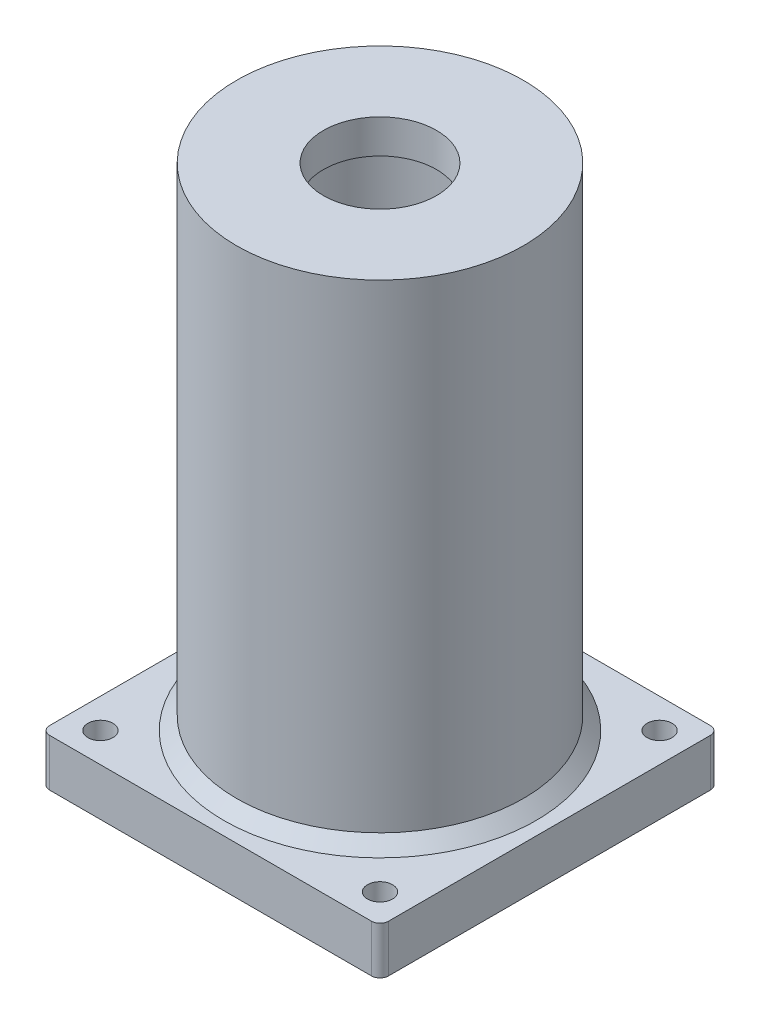
SolidWorks part; units mm, degrees
ref_plane "Front Plane" through (0, 0, 0) normal (0, 0, 1) x (1, 0, 0)
ref_plane "Top Plane" through (0, 0, 0) normal (0, 1, 0) x (1, 0, 0)
ref_plane "Right Plane" through (0, 0, 0) normal (1, 0, 0) x (0, 0, -1)
sketch "Sketch1" plane through (0, 0, 0) normal (0, 1, 0) x (1, 0, 0)
  line L1 (-20, 20) -> (20, 20)
  line L2 (-20, 20) -> (-20, -20)
  line L3 (-20, -20) -> (20, -20)
  line L4 (20, 20) -> (20, -20)
  line L5 (-20, 20) -> (20, -20) construction
  line L6 (-20, -20) -> (20, 20) construction
  circle A0 centre (0, 0) radius 7.875 construction
  circle A1 centre (0, 0) radius 15.875 construction
  point P0 (0, 0)
  dimension "D3" = 15.75
  dimension "D4" = 8
  dimension "D1" = 40
  dimension "D2" = 40
extrude "Boss-Extrude1" add sketch "Sketch1" along normal blind 5.6
sketch "Sketch2" plane through (0, 5.6, 0) normal (0, 1, 0) x (1, 0, 0)
  circle A0 centre (0, 0) radius 9.125
  circle A1 centre (0, 0) radius 16.925
  dimension "D1" = 18.25
  dimension "D2" = 7.8
extrude "Boss-Extrude2" add sketch "Sketch2" along normal blind 54
sketch "Sketch3" plane through (0, 0, 0) normal (0, -1, 0) x (1, 0, 0)
  line L0 (-16.5, 16.5) -> (-16.5, -16.5) construction
  line L1 (-16.5, -16.5) -> (16.5, -16.5) construction
  line L2 (16.5, -16.5) -> (16.5, 16.5) construction
  line L3 (16.5, 16.5) -> (-16.5, 16.5) construction
  line L4 (20, -20) -> (20, 20)
  line L5 (20, 20) -> (-20, 20)
  line L6 (-20, 20) -> (-20, -20)
  line L7 (-20, -20) -> (20, -20)
  line L8 (20, -20) -> (20, 20) construction
  line L9 (20, 20) -> (-20, 20) construction
  line L10 (-20, 20) -> (-20, -20) construction
  line L11 (-20, -20) -> (20, -20) construction
  circle A0 centre (-16.5, -16.5) radius 1.475
  circle A1 centre (-16.5, 16.5) radius 1.475
  circle A2 centre (16.5, 16.5) radius 1.475
  circle A3 centre (16.5, -16.5) radius 1.475
  dimension "D3" = 2.95
  dimension "D1" = 0
  dimension "D2" = 3.5
extrude "Cut-Extrude1" cut sketch "Sketch3" against normal blind 10
fillet "Fillet1" radius 1 4 edges at (20, 2.8, 20) (-20, 2.8, 20) (-20, 2.8, -20) (20, 2.8, -20)
chamfer "Chamfer1" distance 1.5 angle 45 1 edges at (0, 5.6, 16.925)
sketch "Sketch4" plane through (0, 5.6, 0) normal (0, 1, 0) x (1, 0, 0)
  circle A1 centre (0, 0) radius 9.125
  circle A2 centre (0, 0) radius 9.125
  dimension "D1" = 0
extrude "Cut-Extrude2" cut sketch "Sketch4" against normal blind 10
sketch "Sketch5" plane through (0, 59.6, 0) normal (0, 1, 0) x (1, 0, 0)
  circle A0 centre (0, 0) radius 6.675
  circle A1 centre (0, 0) radius 16.925
  circle A2 centre (0, 0) radius 16.925
  circle A3 centre (0, 0) radius 9.125 construction
  dimension "D2" = 33.85
  dimension "D3" = 2.45
  dimension "D1" = 0
extrude "Boss-Extrude3" add sketch "Sketch5" along normal blind 4
